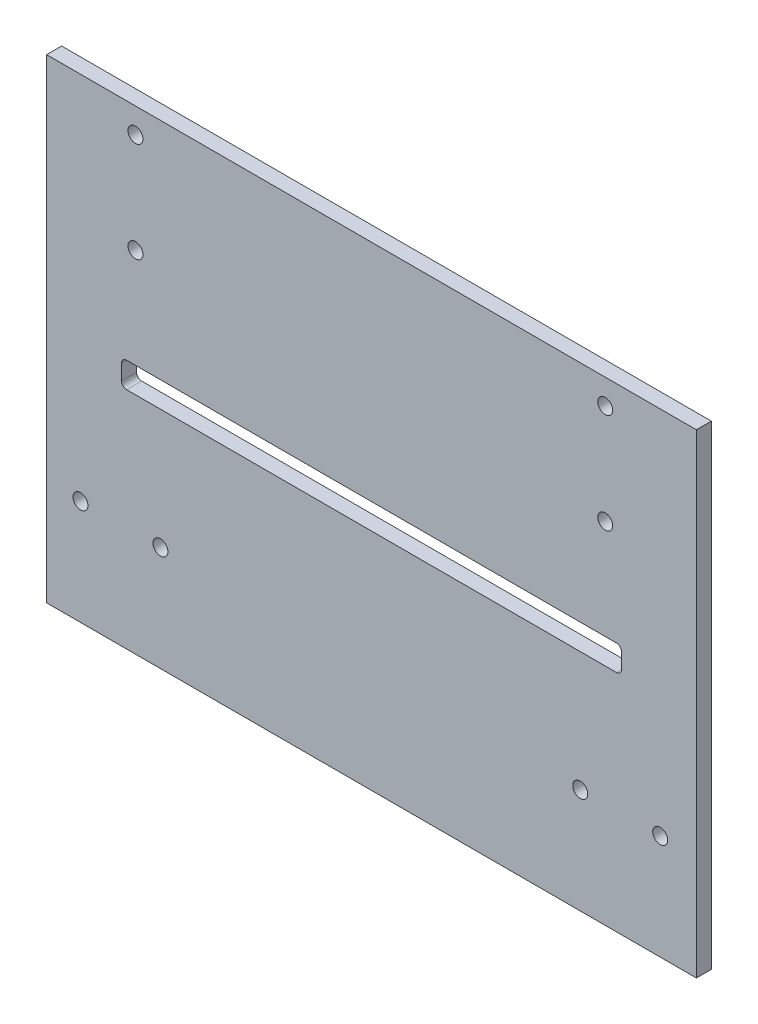
SolidWorks part; units mm, degrees
ref_plane "前视基准面" through (0, 0, 0) normal (0, 0, 1) x (1, 0, 0)
ref_plane "上视基准面" through (0, 0, 0) normal (0, 1, 0) x (1, 0, 0)
ref_plane "右视基准面" through (0, 0, 0) normal (1, 0, 0) x (0, 0, -1)
sketch "草图1" plane through (0, 0, 0) normal (0, 0, 1) x (1, 0, 0)
  line L1 (65, -47.5) -> (-65, -47.5)
  line L2 (65, -47.5) -> (65, 47.5)
  line L3 (65, 47.5) -> (-65, 47.5)
  line L4 (-65, -47.5) -> (-65, 47.5)
  line L5 (65, -47.5) -> (-65, 47.5) construction
  line L6 (65, 47.5) -> (-65, -47.5) construction
  point P0 (0, 0)
  dimension "D1" = 130
  dimension "D2" = 95
extrude "凸台-拉伸1" add sketch "草图1" along normal blind 3
sketch "草图2" plane through (0, 0, 3) normal (0, 0, 1) x (1, 0, 0)
  line L0 (0, -47.5) -> (0, -26.5) construction
  line L1 (-65, -47.5) -> (65, -47.5) construction
  line L2 (0, -26.5) -> (10, -26.5) construction
  circle A0 centre (10, -26.5) radius 1.5
  circle A1 centre (-10, -26.5) radius 1.5
  dimension "D3" = 3
  dimension "D1" = 21
  dimension "D2" = 10
sketch "草图3" plane through (0, 0, 0) normal (0, 0, -1) x (-1, 0, 0)
  circle A0 centre (-57.7671, -26.5) radius 1.5
  circle A1 centre (-41.7671, -26.5) radius 1.5
  circle A2 centre (42.2329, -26.5) radius 1.5
  circle A4 centre (58.2329, -26.5) radius 1.5
extrude "切除-拉伸2" cut sketch "草图3" against normal blind 10
sketch "草图4" plane through (0, 0, 0) normal (0, 0, -1) x (-1, 0, 0)
  circle A0 centre (-46.7671, 42.5) radius 1.5
  circle A1 centre (-46.7671, 22.5) radius 1.5
  circle A2 centre (47.2329, 42.5) radius 1.5
  circle A3 centre (47.2329, 22.5) radius 1.5
extrude "切除-拉伸3" cut sketch "草图4" against normal blind 10
sketch "草图5" plane through (0, 0, 3) normal (0, 0, 1) x (1, 0, 0)
  line L1 (50, -2.55) -> (-50, -2.55)
  line L2 (50, -2.55) -> (50, 2.55)
  line L3 (50, 2.55) -> (-50, 2.55)
  line L4 (-50, -2.55) -> (-50, 2.55)
  line L5 (50, -2.55) -> (-50, 2.55) construction
  line L6 (50, 2.55) -> (-50, -2.55) construction
  point P0 (0, 0)
  dimension "D1" = 5.1
  dimension "D2" = 100
extrude "切除-拉伸4" cut sketch "草图5" against normal blind 10
fillet "圆角1" radius 1 1 edges at (-50, 2.55, 1.5)
fillet "圆角2" radius 1 3 edges at (50, 2.55, 1.5) (50, -2.55, 1.5) (-50, -2.55, 1.5)
